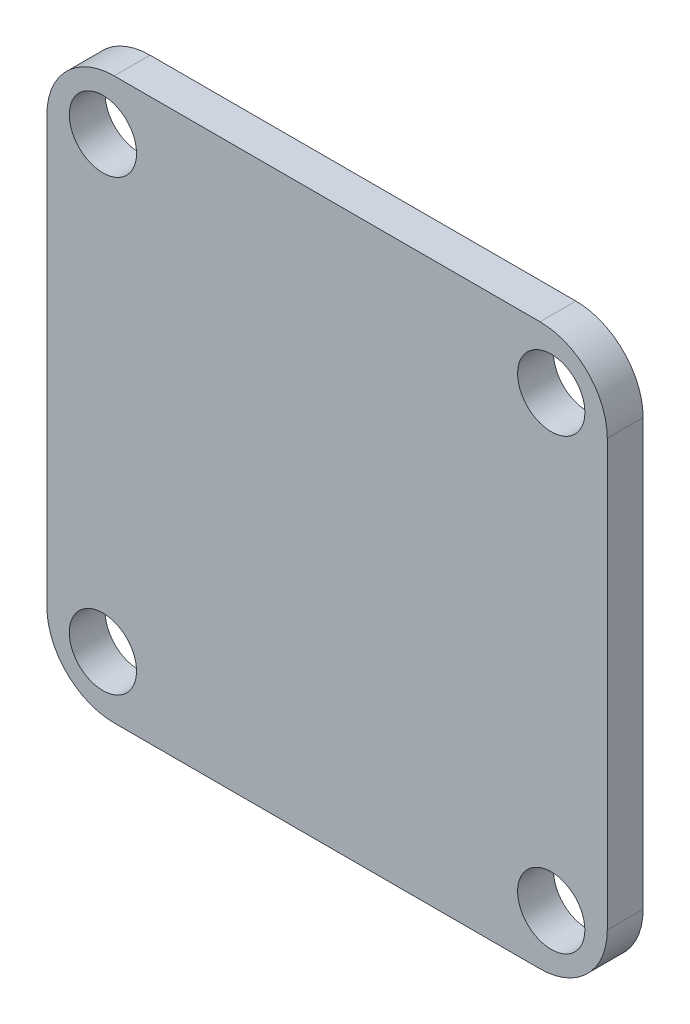
SolidWorks part; units mm, degrees
ref_plane "Front Plane" through (0, 0, 0) normal (0, 0, 1) x (1, 0, 0)
ref_plane "Top Plane" through (0, 0, 0) normal (0, 1, 0) x (1, 0, 0)
ref_plane "Right Plane" through (0, 0, 0) normal (1, 0, 0) x (0, 0, -1)
sketch "Sketch1" plane through (0, 0, 0) normal (0, 0, 1) x (1, 0, 0)
  line L1 (-9.5, -12.5) -> (9.5, -12.5)
  line L2 (-12.5, -9.5) -> (-12.5, 9.5)
  line L3 (-9.5, 12.5) -> (9.5, 12.5)
  line L4 (12.5, -9.5) -> (12.5, 9.5)
  line L5 (-12.5, -12.5) -> (12.5, 12.5) construction
  line L6 (-12.5, 12.5) -> (12.5, -12.5) construction
  line L7 (0, 12.5) -> (0, 0) construction
  line L8 (0, 0) -> (-12.5, 0) construction
  arc A0 (-9.5, -12.5) -> (-12.5, -9.5) centre (-9.5, -9.5) cw
  arc A1 (9.5, -12.5) -> (12.5, -9.5) centre (9.5, -9.5) ccw
  arc A2 (9.5, 12.5) -> (12.5, 9.5) centre (9.5, 9.5) cw
  arc A3 (-12.5, 9.5) -> (-9.5, 12.5) centre (-9.5, 9.5) cw
  circle A4 centre (-10, 10) radius 1.5
  circle A5 centre (10, 10) radius 1.5
  circle A6 centre (10, -10) radius 1.5
  circle A7 centre (-10, -10) radius 1.5
  point P0 (0, 0)
  dimension "D3" = 3
  dimension "D4" = 3
  dimension "D1" = 25
  dimension "D2" = 25
  dimension "D5" = 10
extrude "Boss-Extrude1" add sketch "Sketch1" along normal blind 1.6
